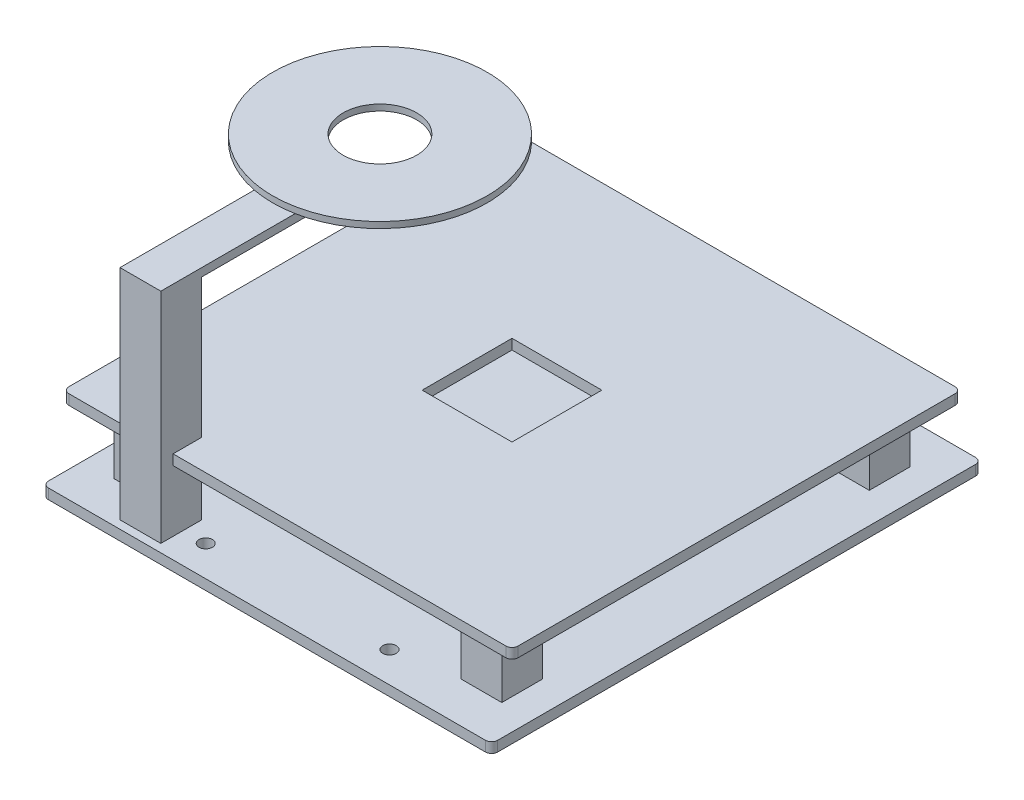
SolidWorks part; units mm, degrees
ref_plane "前视基准面" through (0, 0, 0) normal (0, 0, 1) x (1, 0, 0)
ref_plane "上视基准面" through (0, 0, 0) normal (0, 1, 0) x (1, 0, 0)
ref_plane "右视基准面" through (0, 0, 0) normal (1, 0, 0) x (0, 0, -1)
other "Configuration Table"
sketch "Base Plate Profile" plane through (0, 0, 0) normal (0, 1, 0) x (1, 0, 0)
  line L1 (-110, 120) -> (110, 120)
  line L2 (-110, 120) -> (-110, -120)
  line L3 (-110, -120) -> (110, -120)
  line L4 (110, 120) -> (110, -120)
  point P8 (0, 0)
  dimension "D1" = 110
  dimension "D2" = 220
  dimension "D3" = 120
  dimension "D4" = 240
extrude "Base Plate" add sketch "Base Plate Profile" along normal blind 5
sketch "Standoffs Profile" plane through (0, 0, 0) normal (0, 1, 0) x (1, 0, 0)
  line L1 (-95, 100) -> (-75, 100)
  line L2 (-95, 100) -> (-95, 80)
  line L3 (-95, 80) -> (-75, 80)
  line L4 (-75, 100) -> (-75, 80)
  line L6 (-95, -80) -> (-75, -80)
  line L7 (-95, -80) -> (-95, -100)
  line L8 (-95, -100) -> (-75, -100)
  line L9 (-75, -80) -> (-75, -100)
  line L11 (75, 100) -> (95, 100)
  line L12 (75, 100) -> (75, 80)
  line L13 (75, 80) -> (95, 80)
  line L14 (95, 100) -> (95, 80)
  line L16 (75, -80) -> (95, -80)
  line L17 (75, -80) -> (75, -100)
  line L18 (75, -100) -> (95, -100)
  line L19 (95, -80) -> (95, -100)
  point P32 (0, 0)
  dimension "D1" = 20
  dimension "D2" = 95
  dimension "D3" = 170
  dimension "D4" = 100
  dimension "D5" = 180
extrude "Standoffs" add sketch "Standoffs Profile" along normal blind 30 from offset 5
sketch "Holder Seat Profile" plane through (0, 0, 0) normal (0, 1, 0) x (1, 0, 0)
  line L1 (-110, 110) -> (110, 110)
  line L2 (-110, 110) -> (-110, -110)
  line L3 (-110, -110) -> (110, -110)
  line L4 (110, 110) -> (110, -110)
  line L6 (-22, 22) -> (22, 22)
  line L7 (-22, 22) -> (-22, -22)
  line L8 (-22, -22) -> (22, -22)
  line L9 (22, 22) -> (22, -22)
  point P18 (0, 0)
  dimension "D1" = 88
  dimension "D2" = 110
  dimension "D3" = 132
  dimension "D4" = 220
  dimension "D5" = 88
  dimension "D6" = 110
extrude "Holder Seat" add sketch "Holder Seat Profile" along normal blind 5 from offset 35
sketch "Guide Column Profile" plane through (0, 0, 0) normal (0, 1, 0) x (1, 0, 0)
  line L1 (-75.9869, -96) -> (-55.9869, -96)
  line L2 (-75.9869, -96) -> (-75.9869, -116)
  line L3 (-75.9869, -116) -> (-55.9869, -116)
  line L4 (-55.9869, -96) -> (-55.9869, -116)
  point P8 (0, 0)
  dimension "D1" = 20
  dimension "D2" = 75.9869
  dimension "D3" = 116
extrude "Guide Column" add sketch "Guide Column Profile" along normal blind 107 from offset 5
sketch "Guide Arm Profile" plane through (0, 0, 0) normal (0, 1, 0) x (1, 0, 0)
  line L1 (-75.9869, -38.6861) -> (-55.9869, -38.6861)
  line L2 (-75.9869, -38.6861) -> (-75.9869, -116)
  line L3 (-75.9869, -116) -> (-55.9869, -116)
  line L4 (-55.9869, -38.6861) -> (-55.9869, -116)
  point P10 (0, 0)
  dimension "D1" = 20
  dimension "D2" = 75.9869
  dimension "D3" = 77.3139
  dimension "D4" = 116
extrude "Guide Arm" add sketch "Guide Arm Profile" along normal blind 4 from offset 108
sketch "Guide Seat Profile" plane through (0, 0, 0) normal (0, 1, 0) x (1, 0, 0)
  circle A0 centre (-65.9869, 1.3139) radius 52.5
  circle A1 centre (-65.9869, 1.3139) radius 18
  point P3 (0, 0)
  dimension "D1" = 36
  dimension "D2" = 105
  dimension "D3" = 65.9869
  dimension "D4" = 1.3139
extrude "Guide Seat" add sketch "Guide Seat Profile" along normal blind 3 from offset 112
sketch "Base Fixing Holes Layout" plane through (0, 0, 0) normal (0, 1, 0) x (1, 0, 0)
  circle A0 centre (-45, 105) radius 3.3
  circle A1 centre (-45, -105) radius 3.3
  circle A2 centre (45, 105) radius 3.3
  circle A3 centre (45, -105) radius 3.3
  point P8 (0, 0)
  dimension "D1" = 6.6
  dimension "D2" = 6.6
  dimension "D3" = 6.6
  dimension "D4" = 6.6
  dimension "D5" = 45
  dimension "D6" = 90
  dimension "D7" = 105
  dimension "D8" = 210
extrude "Base Fixing Holes" cut sketch "Base Fixing Holes Layout" against normal mid plane 5 from offset 2.5
fillet "Plate Corner Radii" radius 3 8 edges at (-110, 37.5, -110) (110, 37.5, -110) (110, 37.5, 110) (-110, 37.5, 110) (-110, 2.5, -120) (110, 2.5, -120) (110, 2.5, 120) (-110, 2.5, 120)
